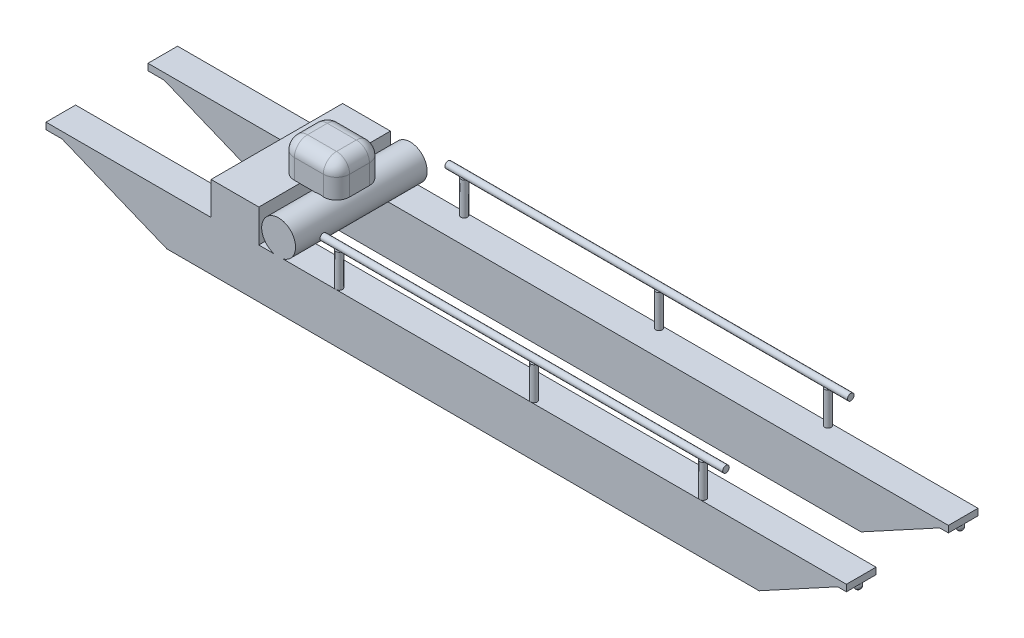
SolidWorks part; units mm, degrees
ref_plane "Alzado" through (0, 0, 0) normal (0, 0, 1) x (1, 0, 0)
ref_plane "Planta" through (0, 0, 0) normal (0, 1, 0) x (1, 0, 0)
ref_plane "Vista lateral" through (0, 0, 0) normal (1, 0, 0) x (0, 0, -1)
sketch "Croquis1" plane through (0, 0, 0) normal (0, 0, 1) x (1, 0, 0)
  line L0 (-12674.457, 0) -> (11655.543, 0)
  line L1 (11655.543, 0) -> (11655.543, -200)
  line L2 (0, -1500) -> (9000, -1500)
  line L3 (0, -1500) -> (-9000, -1500)
  line L4 (9000, -1500) -> (11389.9887, -200)
  line L5 (-9000, -1500) -> (-12184.5294, -200)
  line L6 (11655.543, -200) -> (11389.9887, -200)
  line L7 (-12674.457, -200) -> (-12184.5294, -200)
  line L9 (-12674.457, 0) -> (-12674.457, -200)
  dimension "D1" = 24330
  dimension "D2" = 200
  dimension "D3" = 9000
  dimension "D4" = 9000
  dimension "D5" = 1500
  dimension "D6" = 200
extrude "Saliente-Extruir1" add sketch "Croquis1" along normal blind 900
sketch "Croquis3" plane through (0, -200, 0) normal (0, -1, 0) x (1, 0, 0)
  line L0 (11655.543, 900) -> (11655.543, 0) construction
  circle A0 centre (11555.543, 450) radius 100
  point P4 (11655.543, 450)
  dimension "D1" = 200
  dimension "D2" = 100
extrude "Saliente-Extruir3" add sketch "Croquis3" along normal blind 200
fillet "Redondeo2" radius 100 1 edges at (11655.543, -400, 450)
sketch "Croquis5" plane through (0, -200, 0) normal (0, -1, 0) x (1, 0, 0)
  line L0 (-12674.457, 900) -> (-12674.457, 0) construction
  circle A0 centre (-12574.457, 450) radius 100
  dimension "D1" = 200
  dimension "D2" = 100
extrude "Saliente-Extruir4" add sketch "Croquis5" along normal blind 200
fillet "Redondeo4" radius 100 1 edges at (-12474.457, -400, 450)
sketch "Croquis6" plane through (0, 0, 900) normal (0, 0, 1) x (1, 0, 0)
  line L0 (-12674.457, -200) -> (-12674.457, 0)
  line L1 (-12674.457, 0) -> (11655.543, 0)
  line L2 (11655.543, 0) -> (11655.543, -200)
  line L3 (11655.543, -200) -> (11389.9887, -200)
  line L4 (11389.9887, -200) -> (9000, -1500)
  line L5 (9000, -1500) -> (-9000, -1500)
  line L6 (-9000, -1500) -> (-12184.5294, -200)
  line L7 (-12184.5294, -200) -> (-12674.457, -200)
extrude "Saliente-Extruir5" add sketch "Croquis6" along normal blind 3100
sketch "Croquis7" plane through (0, 0, 0) normal (0, 1, 0) x (1, 0, 0)
  line L0 (-12674.457, -3100) -> (-12674.457, -900)
  line L1 (-12674.457, -4000) -> (-12674.457, 0) construction
  line L3 (-12674.457, -900) -> (11655.543, -900)
  line L4 (11655.543, -4000) -> (11655.543, 0) construction
  line L5 (11655.543, -900) -> (11655.543, -3100)
  line L6 (11655.543, -3100) -> (-12674.457, -3100)
extrude "Cortar-Extruir1" cut sketch "Croquis7" against normal blind 3100
sketch "Croquis8" plane through (0, -200, 0) normal (0, -1, 0) x (1, 0, 0)
  line L0 (-12674.457, 4000) -> (-12674.457, 3100) construction
  line L1 (11655.543, 4000) -> (11655.543, 3100) construction
  circle A0 centre (-12574.457, 3550) radius 100
  circle A1 centre (11555.543, 3550) radius 100
  dimension "D1" = 200
  dimension "D3" = 200
  dimension "D4" = 100
  dimension "D2" = 100
extrude "Saliente-Extruir6" add sketch "Croquis8" along normal blind 200
fillet "Redondeo5" radius 100 2 edges at (-12474.457, -400, 3550) (11655.543, -400, 3550)
sketch "Croquis9" plane through (0, 0, 0) normal (0, 1, 0) x (1, 0, 0)
  line L2 (11655.543, -4000) -> (-12674.457, -4000) construction
  line L3 (-7657.2244, -4000) -> (-7657.2244, 0)
  line L4 (11655.543, 0) -> (-12674.457, 0) construction
  line L6 (-7657.2244, 0) -> (-6205.0141, 0)
  line L7 (-6205.0141, 0) -> (-6205.0141, -4000)
  line L8 (-6205.0141, -4000) -> (-7657.2244, -4000)
extrude "Saliente-Extruir7" add sketch "Croquis9" along normal blind 1000
sketch "Croquis10" plane through (0, 0, 4000) normal (0, 0, 1) x (1, 0, 0)
  circle A0 centre (-5603.7765, 500) radius 515.4202
extrude "Saliente-Extruir8" add sketch "Croquis10" against normal up to surface (4000 mm away)
sketch "Croquis11" plane through (0, 1000, 0) normal (0, 1, 0) x (1, 0, 0)
  line L0 (-6768.9677, -1354.7219) -> (-5088.3563, -1354.7219)
  line L1 (-5088.3563, -4000) -> (-5088.3563, 0) construction
  line L2 (-5088.3563, -1354.7219) -> (-5088.3563, -2755.946)
  line L3 (-5088.3563, -2755.946) -> (-6768.9677, -2755.946)
  line L4 (-6768.9677, -2755.946) -> (-6768.9677, -1354.7219)
  line L5 (-6768.9677, -1354.7219) -> (-6755.9934, -1393.6448)
extrude "Saliente-Extruir9" add sketch "Croquis11" along normal blind 1000
fillet "Redondeo6" radius 400 8 edges at (-6768.9677, 1500, 1354.7219) (-6768.9677, 2000, 2055.3339) (-6768.9677, 1500, 2755.946) (-5928.662, 2000, 1354.7219) (-5088.3563, 1500, 1354.7219) (-5928.662, 2000, 2755.946) (-5088.3563, 1500, 2755.946) (-5088.3563, 2000, 2055.3339)
sketch "Croquis12" plane through (0, 0, 0) normal (0, 1, 0) x (1, 0, 0)
  line L0 (11655.543, -4000) -> (-5478.6446, -4000) construction
  line L1 (11655.543, 0) -> (-5478.6446, 0) construction
  circle A0 centre (-3862.9654, -3900) radius 100
  circle A1 centre (2059.9759, -3900) radius 100
  circle A2 centre (7198.2657, -3900) radius 100
  circle A3 centre (-3862.9654, -100) radius 100
  circle A4 centre (2059.9759, -100) radius 100
  circle A5 centre (7198.2657, -100) radius 100
  dimension "D1" = 200
  dimension "D3" = 200
  dimension "D5" = 200
  dimension "D7" = 200
  dimension "D10" = 200
  dimension "D11" = 200
  dimension "D2" = 100
  dimension "D4" = 100
  dimension "D6" = 100
  dimension "D8" = 100
  dimension "D9" = 100
  dimension "D12" = 100
extrude "Saliente-Extruir10" add sketch "Croquis12" along normal blind 1000
sketch "Croquis13" plane through (11655.543, 0, 0) normal (1, 0, 0) x (0, 0, -1)
  line L0 (-3800, 1000) -> (-4000, 1000) construction
  circle A0 centre (-3900, 1100) radius 100
  circle A1 centre (-104.5759, 1100) radius 100
  dimension "D1" = 200
  dimension "D3" = 200
  dimension "D2" = 100
extrude "Saliente-Extruir11" add sketch "Croquis13" against normal blind 16000 separate body
sketch "Croquis14" plane through (0, 0, 4000) normal (0, 0, 1) x (1, 0, 0)
  line L0 (7895.0616, 1805.867) -> (7895.0616, 470.5308)
  line L1 (7895.0616, 470.5308) -> (11843.5023, 470.5308)
  line L2 (11843.5023, 470.5308) -> (11843.5023, 1805.867)
  line L3 (11843.5023, 1805.867) -> (7895.0616, 1805.867)
extrude "Cortar-Extruir2" cut sketch "Croquis14" against normal blind 16000
